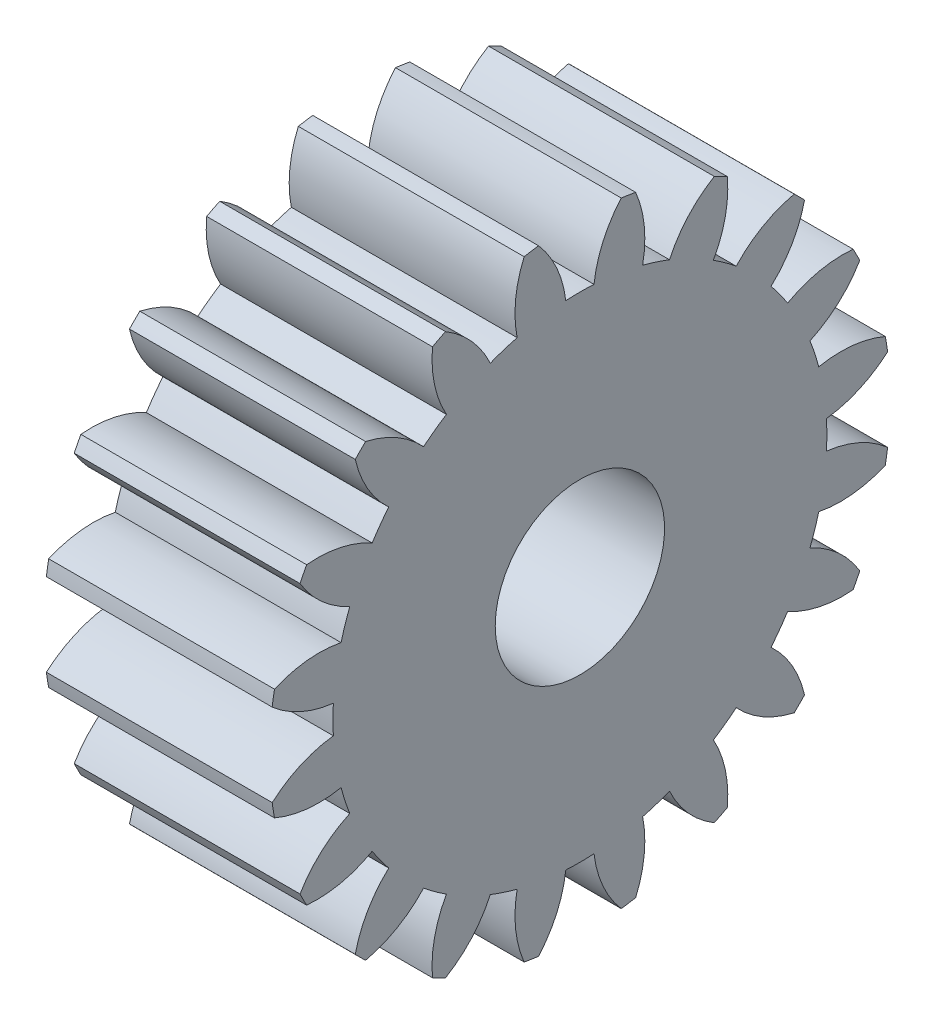
SolidWorks part; units mm, degrees
ref_plane "Plane1" through (0, 0, 0) normal (0, 0, 1) x (1, 0, 0)
ref_plane "Plane2" through (0, 0, 0) normal (0, 1, 0) x (1, 0, 0)
ref_plane "Plane3" through (0, 0, 0) normal (1, 0, 0) x (0, 0, -1)
sketch "HoldingSke" plane through (0, 0, 0) normal (0, 1, 0) x (1, 0, 0)
  line L0 (0, 0) -> (0.9397, -0.342)
  line L1 (-15, 0) -> (100, 0) construction
  line L2 (0, 0) -> (-2.1039, 2.3779)
  line L3 (0, 0) -> (-11.863, 4.5341)
  line L4 (0, 0) -> (8.1152, 2.9537)
  line L5 (0, 0) -> (-46.8476, -17.4728)
  line L6 (0, 0) -> (-8.2896, -5.593)
  line L7 (-2.1039, 2.3779) -> (8.6586, 51.2059)
  line L8 (-76.2, 54.61) -> (-75.2, 54.61)
  line L9 (-71.009, 38.7566) -> (-53.1078, 45.2721)
  line L10 (-76.2, 71.12) -> (104.1128, 71.12)
  line L11 (0, 0) -> (-10, 0)
  line L12 (-76.2, 101.6) -> (-76.162, 101.6)
  line L13 (24.9733, 27.94) -> (52.9518, 28.4284)
  line L14 (24.9733, 27.94) -> (24.9743, 27.94)
  line L15 (24.9733, 27.94) -> (100.4006, 29.5858)
  line L16 (-63.627, -1) -> (-12.827, -1)
  circle A0 centre (0, 0) radius 3
  circle A1 centre (0, 0) radius 8.749
  circle A2 centre (0, 0) radius 37.5
  circle A3 centre (0, 0) radius 3
  dimension "MHD" = 17.498
  dimension "Hub_dia" = 75
  dimension "Bore" = 6
  dimension "MBD" = 6
  dimension "Num_teeth" = 20
  dimension "Pitch" = 1
  dimension "Overall_len" = 50
  dimension "Show_teeth" = 20
  dimension "Thickness" = 10
  dimension "OAL" = 50.0001
  dimension "T_dim" = 1
  dimension "Ap" = 20
  dimension "H" = 19.05
  dimension "Pitch_radius" = 180.3128
  dimension "Width" = 10
  dimension "Backlash" = 0.038
  dimension "Addendum_fac" = 1
  dimension "Dedendum_fac" = 1.25
  dimension "Clearance_fac" = 0.25
  dimension "Dedendum_add" = 0.001
  dimension "Module" = 1
sketch "BasProSke" plane through (0, 0, 0) normal (0, 1, 0) x (1, 0, 0)
  line L0 (-10, 0) -> (60, 0) construction
  line L1 (0, 0) -> (0, 11)
  line L2 (0, 0) -> (10, 0)
  line L3 (10, 0) -> (10, 11)
  line L4 (10, 11) -> (0, 11)
  dimension "Thickness" = 10
  dimension "Diameter" = 22
revolve "Base-Revolve" add sketch "BasProSke" angle 360 about L0
sketch "TooCutSke" plane through (0, 0, 0) normal (1, 0, 0) x (0, 0, -1)
  line L1 (0, 0) -> (0, 107) construction
  line L2 (0, 0) -> (-0.8511, 9.9637) construction
  line L3 (0, 0) -> (-3.1206, 19.7028) construction
  line L4 (-0.8511, 9.9637) -> (-1.5603, 9.8514) construction
  arc A0 (0.4999, 8.7347) -> (-0.4999, 8.7347) centre (0, 0) ccw
  arc A1 (1.4852, 10.9249) -> (-1.4852, 10.9249) centre (0, 0) ccw
  circle A2 centre (0, 0) radius 10 construction
  circle A3 centre (0, 0) radius 9.3969 construction
  arc A4 (-0.4999, 8.7347) -> (-1.4852, 10.9249) centre (-4.4722, 8.2645) ccw
  arc A5 (1.4852, 10.9249) -> (0.4999, 8.7347) centre (4.4722, 8.2645) ccw
  dimension "Root_dia" = 17.498
  dimension "Overcut_dia" = 22.0508
  dimension "Pitch_dia" = 20
  dimension "Base_dia" = 18.7939
  dimension "Flank_rad" = 4
  dimension "Half_ang" = 9
  dimension "Half_CT" = 0.7181
extrude "ToothCut" cut sketch "TooCutSke" along normal through all
fillet "Breaks" [suppressed] radius 0.02
fillet "RootFillets" [suppressed] radius 0.251
pattern_circular "TeethCuts" count 20 every 18 about axis through (-10, 0, 0) along (1, 0, 0) of "ToothCut", "RootFillets", "Breaks"
sketch "HubNeaOneSke" plane through (0, 0, 0) normal (-1, 0, 0) x (0, 0, 1)
  circle A0 centre (0, 0) radius 8.749
  dimension "Diameter" = 17.498
extrude "HubNearOne" [suppressed] add sketch "HubNeaOneSke" along normal blind 40.0001
sketch "HubNeaBotSke" plane through (0, 0, 0) normal (-1, 0, 0) x (0, 0, 1)
  circle A0 centre (0, 0) radius 8.749
  dimension "Diameter" = 17.498
extrude "HubNearBoth" [suppressed] add sketch "HubNeaBotSke" along normal blind 20
ref_plane "FarPln" through (10, 0, 0) normal (1, 0, 0) x (0, 0, -1)
sketch "HubFarSke" plane through (10, 0, 0) normal (1, 0, 0) x (0, 0, -1)
  circle A0 centre (0, 0) radius 8.749
  dimension "Diameter" = 17.498
extrude "HubFar" [suppressed] add sketch "HubFarSke" along normal blind 20
sketch "BorSke" plane through (0, 0, 0) normal (1, 0, 0) x (0, 0, -1)
  circle A0 centre (0, 0) radius 3
  dimension "Diameter" = 6
extrude "Bore" cut sketch "BorSke" along normal mid plane 100.0001
sketch "KeySke" plane through (0, 0, 0) normal (1, 0, 0) x (0, 0, -1)
  line L0 (-1, 0) -> (-1, 4)
  line L1 (-1, 4) -> (1, 4)
  line L2 (1, 4) -> (1, 0)
  line L3 (0, 0) -> (0, 34) construction
  line L4 (-1, 0) -> (1, 0)
  dimension "Offset" = 4
  dimension "Width" = 2
extrude "Keyway" [suppressed] cut sketch "KeySke" along normal mid plane 100.0001
pattern_circular "Keyway2" [suppressed] count 2 every 90 about axis through (-10, 0, 0) along (1, 0, 0)
sketch "Sketch1" plane through (0, 0, 0) normal (0, 1, 0) x (1, 0, 0)
  line L0 (0, 0.4999) -> (0, -0.4999) construction
  line L1 (8, -12.5) -> (12, -12.5)
  line L2 (8, -12.5) -> (8, 12.5)
  line L3 (8, 12.5) -> (12, 12.5)
  line L4 (12, -12.5) -> (12, 12.5)
  point P6 (0, 0)
  point P7 (8, 0)
  dimension "D1" = 8
  dimension "D2" = 4
  dimension "D3" = 25
extrude "Cut-Extrude1" cut sketch "Sketch1" against normal through all both and the other way through all
equation "' \"Module@HoldingSke\" = 6.35"
equation "' \"Num_teeth@HoldingSke\" = 12"
equation "' \"Ap@HoldingSke\" =  20"
equation "' \"Ap@HoldingSke\" = 20"
equation "' \"Width@HoldingSke\" = 0.5 * 25.4"
equation "' \"Hub_dia@HoldingSke\"= 1 * 25.4"
equation "' \"Hub_dia@HoldingSke\" = 1 * 25.4"
equation "' \"Overall_len@HoldingSke\" = 1.0 * 25.4"
equation "' \"Bore@HoldingSke\" = 0.75 * 25.4"
equation "' \"T_dim@HoldingSke\" = 0.1 * 25.4"
equation "' \"Width@KeySke\" = 0.25 * 25.4"
equation "' \"Show_teeth@HoldingSke\" = 13"
equation "' \"Backlash@HoldingSke\" = 0.009 * 25.4"
equation "' \"Addendum_fac@HoldingSke\" = 1.0"
equation "' \"Dedendum_fac@HoldingSke\" = 1.25"
equation "' \"Dedendum_add@HoldingSke\" = 0.00005 * 25.4"
equation "' \"Clearance_fac@HoldingSke\" = 0.25"
equation "\"Pitch@HoldingSke\" = 1 / \"Module@HoldingSke\""
equation "\"Overcut_dia@TooCutSke\" = (\"Num_teeth@HoldingSke\" + 2 * \"Addendum_fac@HoldingSke\") / \"Pitch@HoldingSke\" + 0.002 * 25.4"
equation "\"Pitch_dia@TooCutSke\" = \"Num_teeth@HoldingSke\" / \"Pitch@HoldingSke\""
equation "\"Base_dia@TooCutSke\" = \"Num_teeth@HoldingSke\" / \"Pitch@HoldingSke\" * cos((\"Ap@HoldingSke\"  * 3.14159265 / 180))"
equation "\"Root_dia@TooCutSke\" = (\"Num_teeth@HoldingSke\" + 2) / \"Pitch@HoldingSke\" - 2 * (\"Addendum_fac@HoldingSke\" + \"Dedendum_fac@HoldingSke\") / \"Pitch@HoldingSke\" - \"Dedendum_add@HoldingSke\" * 2"
equation "\"Half_ang@TooCutSke\" = 180 / \"Num_teeth@HoldingSke\""
equation "\"Half_CT@TooCutSke\" = \"Num_teeth@HoldingSke\" / \"Pitch@HoldingSke\" * sin((3.14159265 / 2 / \"Num_teeth@HoldingSke\")) / 2 - 7 * \"Backlash@HoldingSke\" / 4"
equation "\"Flank_rad@TooCutSke\" = \"Num_teeth@HoldingSke\" / \"Pitch@HoldingSke\" / 5"
equation "\"Radius@RootFillets\" = \"Clearance_fac@HoldingSke\" / \"Pitch@HoldingSke\" + \"Dedendum_add@HoldingSke\""
equation "\"Break_rad@Breaks\" = 0.02 / \"Pitch@HoldingSke\""
equation "\"Thickness@HoldingSke\" = \"Width@HoldingSke\""
equation "\"OAL@HoldingSke\" = \"Thickness@HoldingSke\""
equation "\"MHD@HoldingSke\" = (\"Num_teeth@HoldingSke\" + 2) / \"Pitch@HoldingSke\" - 2 * (\"Addendum_fac@HoldingSke\" + \"Dedendum_fac@HoldingSke\")  / \"Pitch@HoldingSke\" - \"Dedendum_add@HoldingSke\" * 2"
equation "\"MBD@HoldingSke\" = (\"Num_teeth@HoldingSke\" + 2) / \"Pitch@HoldingSke\" - 2 * (\"Addendum_fac@HoldingSke\" + \"Dedendum_fac@HoldingSke\")  / \"Pitch@HoldingSke\" - \"Dedendum_add@HoldingSke\" * 2 - 0.002 * 25.4"
equation "\"MHD@HoldingSke\" = ((sgn( \"MHD@HoldingSke\" - \"Hub_dia@HoldingSke\" )-1)*( \"MHD@HoldingSke\" - \"Hub_dia@HoldingSke\" ))/-2+ \"Hub_dia@HoldingSke\""
equation "\"MBD@HoldingSke\" = ((sgn( \"MBD@HoldingSke\" - \"Bore@HoldingSke\" )-1)*( \"MBD@HoldingSke\" - \"Bore@HoldingSke\" ))/-2+ \"Bore@HoldingSke\""
equation "\"OAL@HoldingSke\" = ((sgn( \"OAL@HoldingSke\" - \"Overall_len@HoldingSke\" )+1)*( \"OAL@HoldingSke\" - \"Overall_len@HoldingSke\" ))/2 + \"Overall_len@HoldingSke\" + 0.000002 * 25.4"
equation "\"Num_teeth@TeethCuts\" = int( \"Show_teeth@HoldingSke\" ) + 1"
equation "\"Num_teeth@TeethCuts\" = ((sgn( \"Num_teeth@TeethCuts\" - \"Num_teeth@HoldingSke\" )-1)*( \"Num_teeth@TeethCuts\" - \"Num_teeth@HoldingSke\" ))/-2+ \"Num_teeth@HoldingSke\""
equation "\"Num_teeth@TeethCuts\" = ((sgn( \"Num_teeth@TeethCuts\" - 2.0)+1)*( \"Num_teeth@TeethCuts\" - 2.0))/2 +2.0"
equation "\"Angle@TeethCuts\" = 360.0 / \"Num_teeth@HoldingSke\""
equation "\"Diameter@BasProSke\" = (\"Num_teeth@HoldingSke\" + 2 * \"Addendum_fac@HoldingSke\") / \"Pitch@HoldingSke\""
equation "\"Thickness@BasProSke\"  = \"Thickness@HoldingSke\""
equation "' \"Fillet_rad@BasProSke\" =  \"Thickness@HoldingSke\" * 0.05"
equation "' \"Fillet_rad@BasProSke\" = \"Thickness@HoldingSke\" * 0.05"
equation "\"MHD@HoldingSke\" = ((sgn( \"MHD@HoldingSke\" - \"Root_dia@TooCutSke\" )-1)*( \"MHD@HoldingSke\" - \"Root_dia@TooCutSke\" ))/-2+ \"Root_dia@TooCutSke\""
equation "\"Diameter@HubNeaOneSke\" = \"MHD@HoldingSke\""
equation "\"Length@HubNearOne\" = \"OAL@HoldingSke\" - \"Thickness@BasProSke\""
equation "\"Diameter@HubNeaBotSke\" = \"MHD@HoldingSke\""
equation "\"Length@HubNearBoth\" = ( \"OAL@HoldingSke\" - \"Thickness@BasProSke\" ) / 2.0"
equation "\"Thickness@FarPln\" = \"Thickness@BasProSke\""
equation "\"Diameter@HubFarSke\" = \"MHD@HoldingSke\""
equation "\"Length@HubFar\" = ( \"OAL@HoldingSke\" - \"Thickness@BasProSke\" ) / 2.0"
equation "\"Diameter@BorSke\" = \"MBD@HoldingSke\""
equation "\"D1@Bore\" = \"OAL@HoldingSke\" * 2.0"
equation "\"D1@Keyway\" = \"OAL@HoldingSke\" * 2.0"
equation "\"Offset@KeySke\" = \"T_dim@HoldingSke\" + \"MBD@HoldingSke\" / 2.0"
